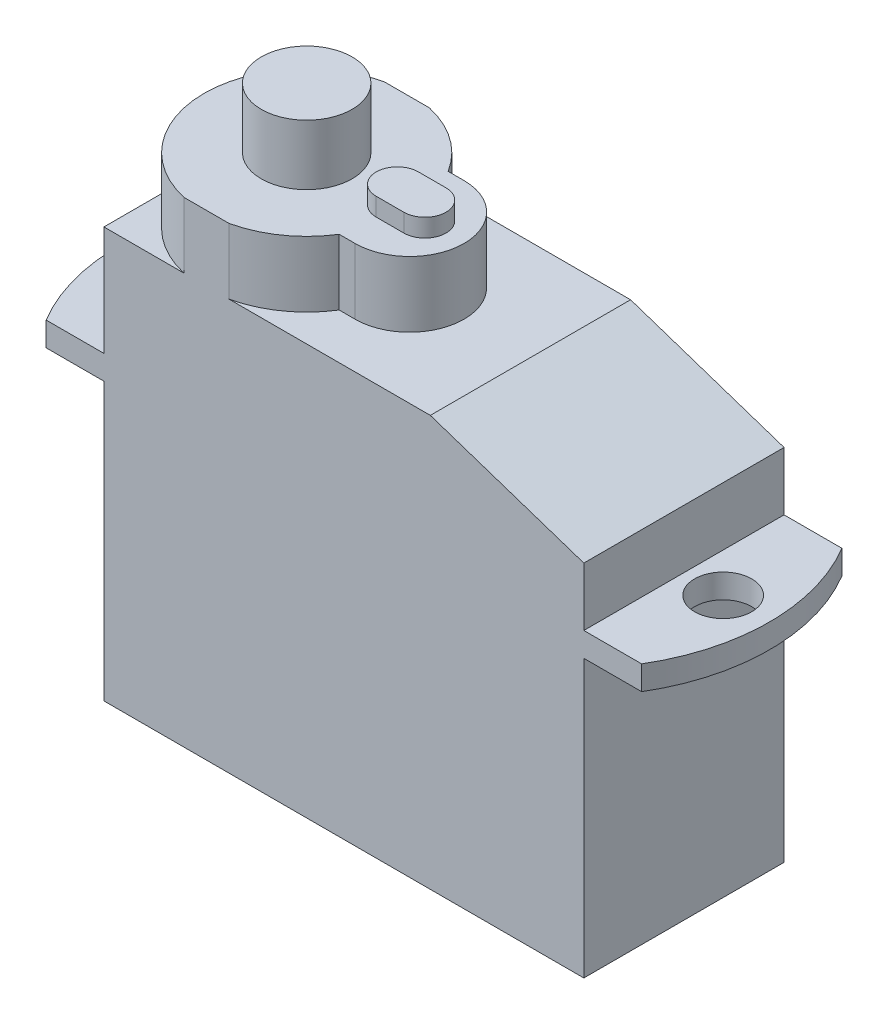
SolidWorks part; units mm, degrees
ref_plane "Front Plane" through (0, 0, 0) normal (0, 0, 1) x (1, 0, 0)
ref_plane "Top Plane" through (0, 0, 0) normal (0, 1, 0) x (1, 0, 0)
ref_plane "Right Plane" through (0, 0, 0) normal (1, 0, 0) x (0, 0, -1)
sketch "Sketch1" plane through (0, 0, 0) normal (0, 1, 0) x (1, 0, 0)
  line L1 (-20.25, 0) -> (0, 0)
  line L2 (-20.25, 0) -> (-20.25, -8.45)
  line L3 (-20.25, -8.45) -> (0, -8.45)
  line L4 (0, 0) -> (0, -8.45)
  dimension "D1" = 20.25
  dimension "D2" = 8.45
extrude "Boss-Extrude1" add sketch "Sketch1" along normal blind 12.7
sketch "Sketch2" plane through (0, 0, 0) normal (1, 0, 0) x (0, 0, -1)
  line L0 (-8.45, 12.7) -> (-8.45, 0) construction
  line L1 (0, 12.7) -> (-8.45, 12.7)
  line L2 (0, 12.7) -> (0, 11.684)
  line L3 (0, 11.684) -> (-8.45, 11.684)
  line L4 (-8.45, 12.7) -> (-8.45, 11.684)
  dimension "D1" = 1.016
extrude "Boss-Extrude2" add sketch "Sketch2" along normal blind 3.61
sketch "Sketch3" plane through (0, 12.7, 0) normal (0, 1, 0) x (1, 0, 0)
  line L0 (0, 0) -> (-20.25, 0) construction
  line L1 (-10.125, 0) -> (-10.125, -8.45) construction
  line L2 (-20.25, -8.45) -> (3.61, -8.45) construction
  line L3 (-10.125, -4.225) -> (1.655, -4.225) construction
  line L4 (3.61, 0) -> (-20.25, 0) construction
  line L5 (2.44, 0) -> (2.44, -8.45) construction
  line L6 (3.61, 0) -> (3.61, -8.45) construction
  circle A0 centre (1.655, -4.225) radius 1.205
  arc A1 (2.44, -8.45) -> (2.44, 0) centre (-4.6035, -4.225) ccw
  point P16 (3.61, -4.225)
  line M2 (-20.25, -8.45) -> (3.61, -8.45)
  line M3 (3.61, -8.45) -> (3.61, 0)
  line M4 (3.61, 0) -> (-20.25, 0)
  dimension "D3" = 2.41
  dimension "D1" = 11.78
  dimension "D2" = 2.44
extrude "Cut-Extrude1" cut sketch "Sketch3" against normal up to next contours A1 M2 M3 | A1 M3 M4 | A0
ref_plane "Plane2" through (-10.125, 0, 0) normal (1, 0, 0) x (0, 0, -1)
mirror "Mirror1" about plane through (-10.125, 0, 0) normal (1, 0, 0) of "Cut-Extrude1", "Boss-Extrude2"
sketch "Sketch4" plane through (0, 12.7, 0) normal (0, 1, 0) x (1, 0, 0)
  line L0 (-22.69, -8.45) -> (2.44, -8.45) construction
  line L1 (0, 0) -> (-20.25, 0)
  line L2 (0, 0) -> (0, -8.45)
  line L3 (0, -8.45) -> (-20.25, -8.45)
  line L4 (-20.25, 0) -> (-20.25, -8.45)
  line L5 (-10.125, -4.6694) -> (0, -4.6694) construction
  line L6 (-10.125, -4.6476) -> (-10.125, 4.6476) construction
  line L7 (-10.125, -4.6694) -> (-20.25, -4.6694) construction
extrude "Boss-Extrude3" add sketch "Sketch4" along normal blind 4.6228
chamfer "Chamfer1" distance 2.159 distance2 6.477 1 edges at (0, 17.3228, 4.225)
sketch "Sketch5" plane through (0, 17.3228, 0) normal (0, 1, 0) x (1, 0, 0)
  line L0 (-20.25, -4.225) -> (-15.9193, -4.225) construction
  line L1 (-20.25, 0) -> (-20.25, -8.45) construction
  line L2 (-20.25, -4.225) -> (-14.0016, -4.225) construction
  circle A0 centre (-15.9193, -4.225) radius 1.9177
  dimension "D1" = 3.8354
  dimension "D2" = 6.2484
extrude "Boss-Extrude4" add sketch "Sketch5" along normal blind 5.3086
sketch "Sketch6" plane through (0, 17.3228, 0) normal (0, 1, 0) x (1, 0, 0)
  line L0 (-20.25, 0) -> (-20.25, -8.45) construction
  line L1 (-6.477, 0) -> (-20.25, 0) construction
  line L2 (-16.8703, 0) -> (-14.9683, 0)
  line L3 (-16.8703, -8.45) -> (-14.9683, -8.45)
  line L4 (-20.25, -8.45) -> (-6.477, -8.45) construction
  line L5 (-20.25, -4.225) -> (-9.2772, -4.225) construction
  line L6 (-11.5759, -1.9263) -> (-12.249, -1.9263)
  line L7 (-11.5759, -6.5237) -> (-12.249, -6.5237)
  circle A0 centre (-15.9193, -4.225) radius 4.3307 construction
  arc A1 (-16.8703, -8.45) -> (-16.8703, 0) centre (-15.9193, -4.225) cw
  arc A2 (-14.9683, 0) -> (-14.9683, -8.45) centre (-15.9193, -4.225) cw
  arc A3 (-11.5759, -1.9263) -> (-11.5759, -6.5237) centre (-11.5759, -4.225) cw
  line M1 (-20.25, -8.45) -> (-6.477, -8.45)
  line M3 (-6.477, 0) -> (-20.25, 0)
  circle M5 centre (-15.9193, -4.225) radius 1.9177
  dimension "D2" = 2.2987
  dimension "D1" = 10.9728
extrude "Boss-Extrude5" add sketch "Sketch6" along normal blind 2.7686 contours A3 L6 A2 L7 | A2 A1 M3 M1 M5
sketch "Sketch7" plane through (0, 20.0914, 0) normal (0, 1, 0) x (1, 0, 0)
  line L0 (-12.9856, -4.225) -> (-10.0392, -4.225) construction
  line L1 (-12.0951, -3.3345) -> (-10.9297, -3.3345)
  line L2 (-10.9297, -5.1155) -> (-12.0951, -5.1155)
  line L3 (-10.0392, -4.225) -> (-9.2772, -4.225)
  arc A0 (-10.9297, -3.3345) -> (-10.9297, -5.1155) centre (-10.9297, -4.225) cw
  arc A1 (-12.0951, -3.3345) -> (-12.0951, -5.1155) centre (-12.0951, -4.225) ccw
  arc A2 (-11.5759, -6.5237) -> (-11.5759, -1.9263) centre (-11.5759, -4.225) ccw construction
  point P8 (-9.2772, -4.225)
  dimension "D1" = 2.9464
  dimension "D2" = 0.762
extrude "Boss-Extrude6" add sketch "Sketch7" along normal blind 0.762 contours L0 A1 L2 A0 | A1 L0 A0 L1
sketch "Sketch8" plane through (-20.25, 0, 0) normal (-1, 0, 0) x (0, 0, 1)
  line L0 (0, 0) -> (8.45, 0) construction
  line L1 (2.955, 0) -> (5.495, 0)
  line L2 (2.955, 0) -> (2.955, 0.8636)
  line L3 (2.955, 0.8636) -> (5.495, 0.8636)
  line L4 (5.495, 0) -> (5.495, 0.8636)
  line L5 (5.495, 0) -> (8.45, 0) construction
  line L6 (2.955, 0) -> (0, 0) construction
  dimension "D1" = 2.54
  dimension "D2" = 0.8636
extrude "Cut-Extrude2" cut sketch "Sketch8" against normal blind 1.6002
sketch "Sketch9" plane through (-18.6498, 0, 0) normal (-1, 0, 0) x (0, 0, 1)
  line L0 (5.495, 0.4318) -> (5.3426, 0.4318) construction
  line L1 (5.495, 0) -> (5.495, 0.8636) construction
  line L2 (2.955, 0.4318) -> (3.1074, 0.4318) construction
  line L3 (2.955, 0.8636) -> (2.955, 0) construction
  circle A0 centre (3.4884, 0.4318) radius 0.381
  circle A1 centre (4.225, 0.4354) radius 0.381
  circle A2 centre (4.9616, 0.4318) radius 0.381
  dimension "D1" = 0.762
  dimension "D2" = 0.7366
  dimension "D3" = 0.7366
extrude "Boss-Extrude9" add sketch "Sketch9" along normal blind 1.6002 contours A2 A1 A0 | A1 A0 | A0 A1 | A1 A2 | A1 A2
